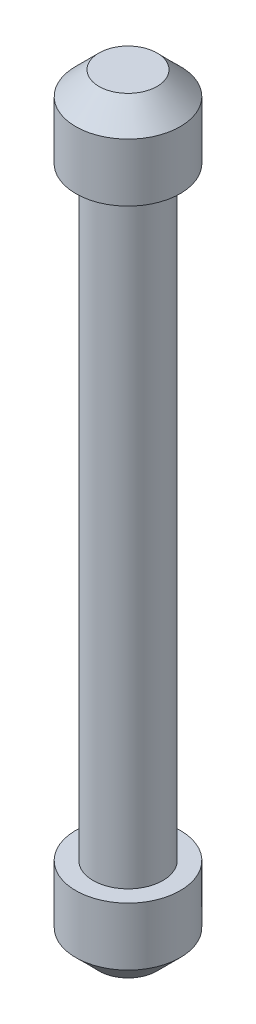
SolidWorks part; units mm, degrees
ref_plane "Front" through (0, 0, 0) normal (0, 0, 1) x (1, 0, 0)
ref_plane "Top" through (0, 0, 0) normal (0, 1, 0) x (1, 0, 0)
ref_plane "Right" through (0, 0, 0) normal (1, 0, 0) x (0, 0, -1)
sketch "Sketch1" plane through (0, 0, 0) normal (0, 1, 0) x (1, 0, 0)
  circle A0 centre (0, 0) radius 2.25
  dimension "D1" = 4.5
extrude "Boss-Extrude1" add sketch "Sketch1" along normal blind 3.5
sketch "Sketch2" plane through (0, 0, 0) normal (0, -1, 0) x (1, 0, 0)
  circle A0 centre (0, 0) radius 1.5
  dimension "D1" = 3
extrude "Boss-Extrude2" add sketch "Sketch2" along normal blind 26
ref_plane "Plane1" through (0, -11.25, 0) normal (0, -1, 0) x (-1, 0, 0)
sketch "Sketch3" plane through (0, -26, 0) normal (0, -1, 0) x (1, 0, 0)
  circle A0 centre (0, 0) radius 2.25 construction
  circle A1 centre (0, 0) radius 2.25
extrude "Boss-Extrude3" add sketch "Sketch3" along normal blind 3.5
chamfer "Chamfer1" distance 1 angle 45 2 edges at (0, -29.5, -2.25) (0, 3.5, 2.25)
